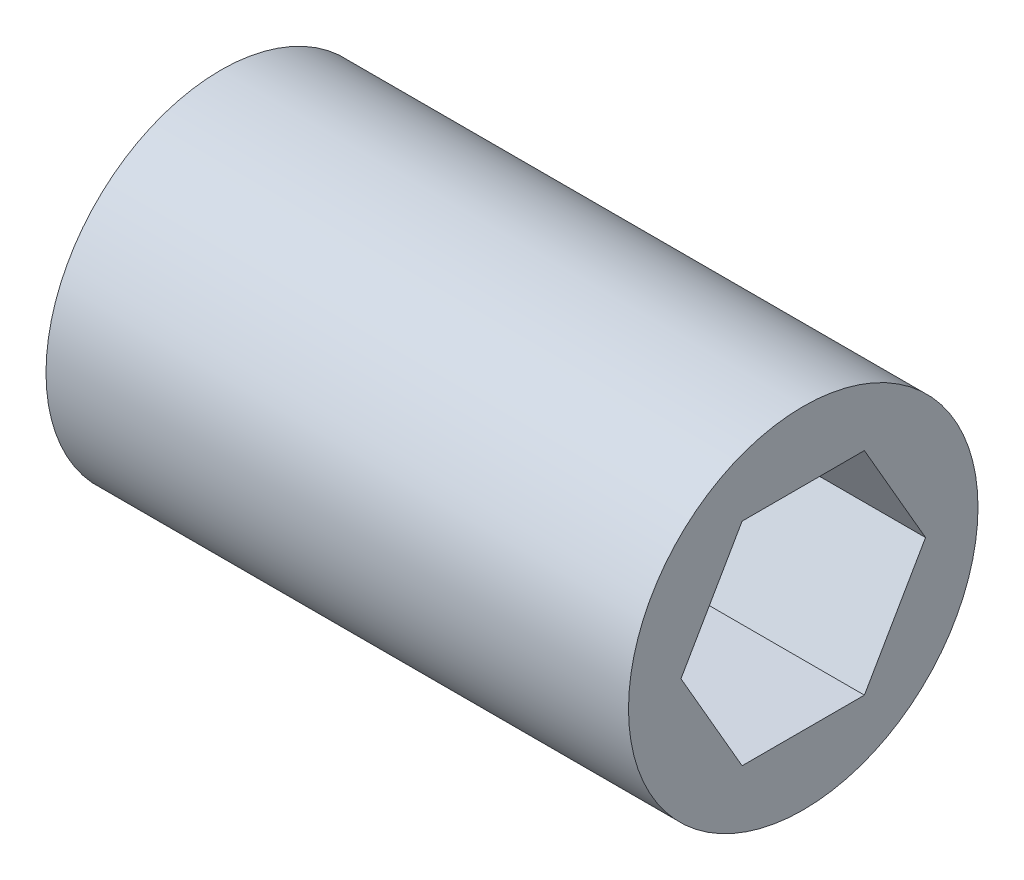
SolidWorks part; units mm, degrees
material "PVC Rigid"
ref_plane "Front Plane" through (0, 0, 0) normal (0, 0, 1) x (1, 0, 0)
ref_plane "Top Plane" through (0, 0, 0) normal (0, 1, 0) x (1, 0, 0)
ref_plane "Right Plane" through (0, 0, 0) normal (1, 0, 0) x (0, 0, -1)
sketch "Sketch1" plane through (0, 0, 0) normal (1, 0, 0) x (0, 0, -1)
  line L1 (3.6662, 6.35) -> (-3.6662, 6.35)
  line L2 (-3.6662, 6.35) -> (-7.3323, 0)
  line L3 (-7.3323, 0) -> (-3.6662, -6.35)
  line L4 (-3.6662, -6.35) -> (3.6662, -6.35)
  line L5 (3.6662, -6.35) -> (7.3323, 0)
  line L6 (7.3323, 0) -> (3.6662, 6.35)
  circle A0 centre (0, 0) radius 6.35 construction
  circle A1 centre (0, 0) radius 10.4775
  dimension "D2" = 20.955
  dimension "D1" = 12.7
extrude "Boss-Extrude1" add sketch "Sketch1" along normal mid plane 34.925
